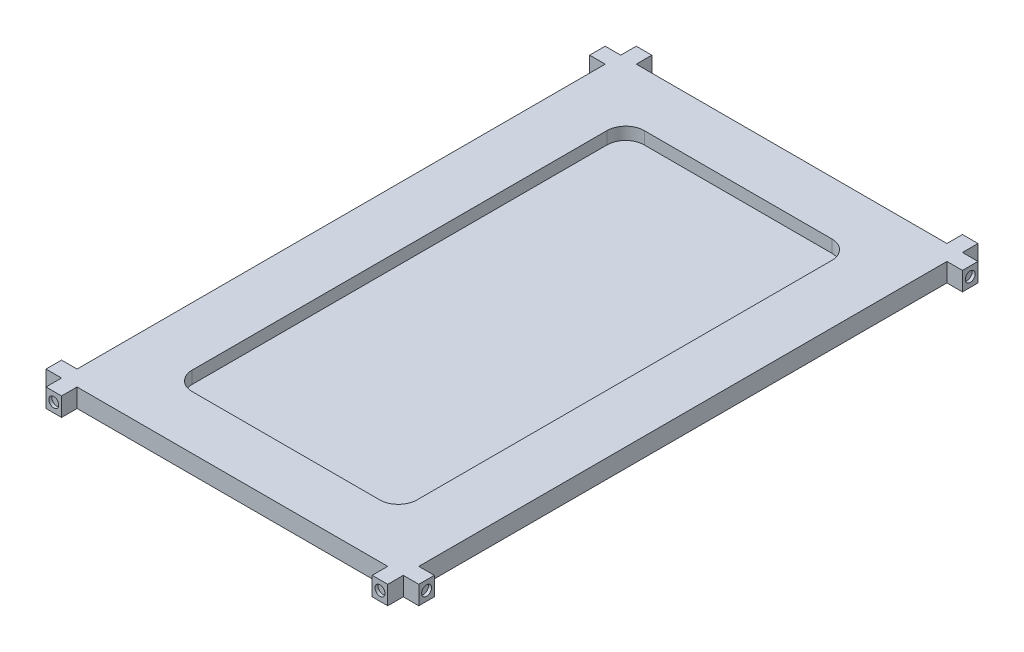
SolidWorks part; units mm, degrees
ref_plane "前视基准面" through (0, 0, 0) normal (0, 0, 1) x (1, 0, 0)
ref_plane "上视基准面" through (0, 0, 0) normal (0, 1, 0) x (1, 0, 0)
ref_plane "右视基准面" through (0, 0, 0) normal (1, 0, 0) x (0, 0, -1)
sketch "草图1" plane through (0, 0, 0) normal (0, 1, 0) x (1, 0, 0)
  line L1 (-275, -450) -> (275, -450)
  line L2 (-275, -450) -> (-275, 450)
  line L3 (-275, 450) -> (275, 450)
  line L4 (275, -450) -> (275, 450)
  line L5 (-275, -450) -> (275, 450) construction
  line L6 (-275, 450) -> (275, -450) construction
  point P0 (0, 0)
  dimension "D1" = 550
  dimension "D2" = 900
extrude "凸台-拉伸1" add sketch "草图1" along normal blind 10 and the other way blind 20
sketch "草图6" plane through (0, 10, 0) normal (0, 1, 0) x (1, 0, 0)
  line L0 (0, 495.3834) -> (0, 0) construction
  line L1 (-604.0385, 0) -> (614.1856, 0) construction
  line L2 (-150.9347, 363.7927) -> (150.9347, 363.7927)
  line L3 (-180.9347, 333.7927) -> (-180.9347, -333.7927)
  line L4 (-150.9347, -363.7927) -> (150.9347, -363.7927)
  line L5 (180.9347, 333.7927) -> (180.9347, -333.7927)
  line L6 (0, -363.7927) -> (0, -482.0205) construction
  arc A0 (-150.9347, 363.7927) -> (-180.9347, 333.7927) centre (-150.9347, 333.7927) ccw
  arc A1 (150.9347, 363.7927) -> (180.9347, 333.7927) centre (150.9347, 333.7927) cw
  arc A2 (-150.9347, -363.7927) -> (-180.9347, -333.7927) centre (-150.9347, -333.7927) cw
  arc A3 (150.9347, -363.7927) -> (180.9347, -333.7927) centre (150.9347, -333.7927) ccw
extrude "切除-拉伸4" cut sketch "草图6" against normal blind 20
sketch "草图7" plane through (0, -20, 0) normal (0, -1, 0) x (1, 0, 0)
  line L0 (0, 0) -> (-215, 0) construction
  line L1 (-215, 0) -> (-215, 300) construction
  line L2 (0, 0) -> (0, 132.0698) construction
  circle A0 centre (-215, 300) radius 50
  circle A1 centre (-215, -300) radius 50
  circle A2 centre (215, -300) radius 50
  circle A3 centre (215, 300) radius 50
extrude "切除-拉伸5" cut sketch "草图7" against normal blind 5
sketch "草图8" plane through (0, -20, 0) normal (0, -1, 0) x (1, 0, 0)
  line L16 (0, 0) -> (0, 193.6274) construction
  line L17 (0, 0) -> (-162.939, 0) construction
  line L26 (-250, -475) -> (-250, -450) construction
  line L27 (-275, -475) -> (-250, -475) construction
  line L28 (-275, -450) -> (-275, -475) construction
  line L29 (-300, -425) -> (-275, -425) construction
  line L30 (-300, -450) -> (-300, -425) construction
  line L31 (-275, -450) -> (-300, -450) construction
  line L40 (-275, -425) -> (-275, -450)
  line L41 (-250, -450) -> (-275, -450)
  line L42 (-250, -475) -> (-250, -450)
  line L43 (-275, -475) -> (-250, -475)
  line L44 (-275, -450) -> (-275, -475)
  line L45 (-300, -450) -> (-275, -450)
  line L46 (-300, -425) -> (-300, -450)
  line L47 (-275, -425) -> (-300, -425)
extrude "凸台-拉伸2" add sketch "草图8" against normal blind 30
sketch "草图9" plane through (-300, 0, 0) normal (-1, 0, 0) x (0, 0, 1)
  line L0 (-437.5, 10) -> (-437.5, -20) construction
  line L1 (-425, 10) -> (-450, 10) construction
  line L2 (-425, -20) -> (-450, -20) construction
  circle A0 centre (-437.5, -5) radius 8
extrude "切除-拉伸6" cut sketch "草图9" against normal blind 5
sketch "草图10" plane through (0, 0, -475) normal (0, 0, -1) x (-1, 0, 0)
  line L0 (262.5, 10) -> (262.5, -20) construction
  line L1 (275, 10) -> (250, 10) construction
  line L2 (275, -20) -> (250, -20) construction
  circle A0 centre (262.5, -5) radius 8
extrude "切除-拉伸7" cut sketch "草图10" against normal blind 5
mirror "镜向1" about plane through (0, 0, 0) normal (1, 0, 0) of "切除-拉伸6", "凸台-拉伸2", "切除-拉伸7"
mirror "镜向2" about plane through (0, 0, 0) normal (0, 0, 1) of "切除-拉伸6", "凸台-拉伸2", "切除-拉伸7", "镜向1"
